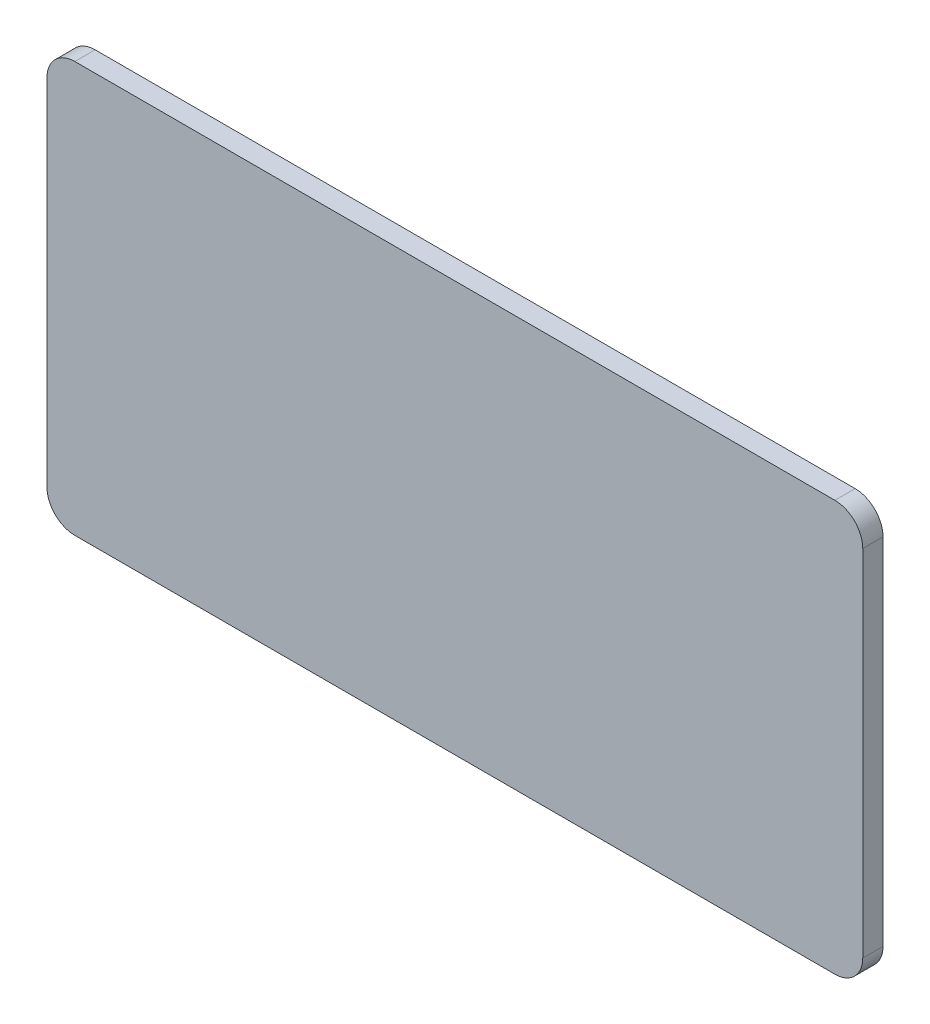
SolidWorks part; units mm, degrees
material "ГОСТ 10007-80 Фторопласт-4"
ref_plane "Front Plane" through (0, 0, 0) normal (0, 0, 1) x (1, 0, 0)
ref_plane "Top Plane" through (0, 0, 0) normal (0, 1, 0) x (1, 0, 0)
ref_plane "Right Plane" through (0, 0, 0) normal (1, 0, 0) x (0, 0, -1)
sketch "Sketch1" plane through (0, 0, 0) normal (0, 0, 1) x (1, 0, 0)
  line L1 (161, 70) -> (161, -70)
  line L2 (150, -81) -> (-150, -81) construction
  line L3 (150, -81) -> (-150, -81)
  line L4 (-161, -70) -> (-161, 70) construction
  line L5 (-161, -70) -> (-161, 70)
  line L6 (-150, 81) -> (0, 81) construction
  line L7 (-150, 81) -> (0, 81)
  line L8 (0, 81) -> (150, 81) construction
  line L9 (0, 81) -> (150, 81)
  arc A0 (150, -81) -> (161, -70) centre (150, -70) ccw construction
  arc A1 (150, -81) -> (161, -70) centre (150, -70) ccw
  arc A2 (-161, -70) -> (-150, -81) centre (-150, -70) ccw construction
  arc A3 (-161, -70) -> (-150, -81) centre (-150, -70) ccw
  arc A4 (-150, 81) -> (-161, 70) centre (-150, 70) ccw construction
  arc A5 (-150, 81) -> (-161, 70) centre (-150, 70) ccw
  arc A6 (161, 70) -> (150, 81) centre (150, 70) ccw construction
  arc A7 (161, 70) -> (150, 81) centre (150, 70) ccw
extrude "Boss-Extrude1" add sketch "Sketch1" along normal up to surface (8 mm away)
